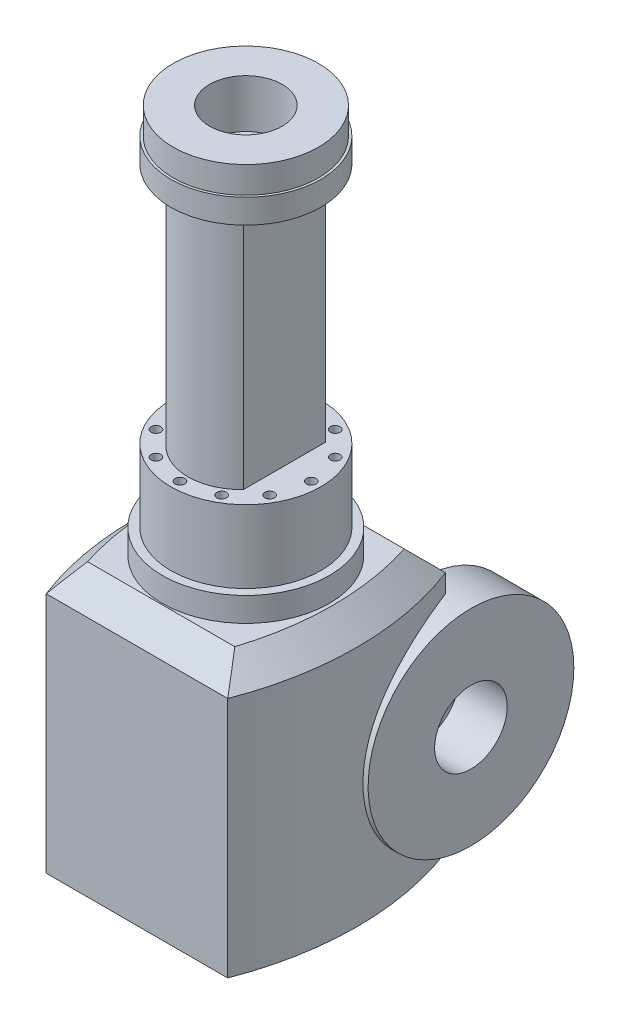
SolidWorks part; units mm, degrees
ref_plane "Front Plane" through (0, 0, 0) normal (0, 0, 1) x (1, 0, 0)
ref_plane "Top Plane" through (0, 0, 0) normal (0, 1, 0) x (1, 0, 0)
ref_plane "Right Plane" through (0, 0, 0) normal (1, 0, 0) x (0, 0, -1)
sketch "Sketch1" plane through (0, 0, 0) normal (0, 1, 0) x (1, 0, 0)
  line L0 (0, 45) -> (0, -45) construction
  line L1 (-66.3108, 0) -> (66.3108, 0) construction
  line L2 (-37.5, 45) -> (37.5, 45)
  line L3 (-37.5, -45) -> (37.5, -45)
  arc A0 (-37.5, 45) -> (-37.5, -45) centre (79.119, 0) ccw
  arc A1 (37.5, 45) -> (37.5, -45) centre (-79.119, 0) cw
  point P4 (0, 0)
  point P8 (0, 0)
  dimension "D4" = 125
  dimension "D1" = 75
  dimension "D2" = 45
  dimension "D3" = 90
extrude "Boss-Extrude1" add sketch "Sketch1" along normal blind 100
sketch "Sketch2" plane through (0, 100, 0) normal (0, 1, 0) x (1, 0, 0)
  line L2 (-37.5, -45) -> (37.5, -45)
  line L3 (37.5, 45) -> (-37.5, 45)
  line L4 (-37.5, -45) -> (37.5, -45)
  line L5 (37.5, 45) -> (-37.5, 45)
  arc A2 (-37.5, 45) -> (-37.5, -45) centre (79.119, 0) ccw
  arc A3 (37.5, -45) -> (37.5, 45) centre (-79.119, 0) ccw
  arc A4 (-37.5, 45) -> (-37.5, -45) centre (79.119, 0) ccw
  arc A5 (37.5, -45) -> (37.5, 45) centre (-79.119, 0) ccw
  dimension "D1" = 0
extrude "Boss-Extrude2" add sketch "Sketch2" along normal blind 10 draft 45
sketch "Sketch3" plane through (0, 110, 0) normal (0, 1, 0) x (1, 0, 0)
  circle A0 centre (0, 0) radius 34.5
  dimension "D1" = 69
extrude "Boss-Extrude3" add sketch "Sketch3" along normal blind 10
sketch "Sketch4" plane through (0, 120, 0) normal (0, 1, 0) x (1, 0, 0)
  circle A0 centre (0, 0) radius 31
  dimension "D1" = 62
extrude "Boss-Extrude4" add sketch "Sketch4" along normal blind 30
sketch "Sketch5" plane through (0, 150, 0) normal (0, 1, 0) x (1, 0, 0)
  line L0 (27, 0) -> (0, 0) construction
  circle A0 centre (27, 0) radius 2
  dimension "D2" = 4
  dimension "D1" = 27
extrude "Cut-Extrude1" cut sketch "Sketch5" against normal blind 5
pattern_circular "CirPattern1" count 12 over 360 about axis through (-0.1129, 0, 0) along (0, 1, 0) of "Cut-Extrude1"
sketch "Sketch6" plane through (0, 150, 0) normal (0, 1, 0) x (1, 0, 0)
  line L0 (-18.5252, 0) -> (17.8556, 0) construction
  line L1 (0, 21.134) -> (0, -18.856) construction
  line L2 (-16, -17) -> (-16, 17)
  line L3 (16, -17) -> (16, 17)
  arc A0 (-16, 17) -> (16, 17) centre (0, 1.9003) cw
  arc A1 (-16, -17) -> (16, -17) centre (0, -1.9003) ccw
  point P8 (-16, 0)
  dimension "D3" = 22
  dimension "D1" = 34
  dimension "D2" = 16
extrude "Boss-Extrude5" add sketch "Sketch6" along normal blind 100
sketch "Sketch7" plane through (0, 250, 0) normal (0, 1, 0) x (1, 0, 0)
  circle A0 centre (0, 0) radius 31
  dimension "D1" = 62
extrude "Boss-Extrude6" add sketch "Sketch7" along normal blind 10
sketch "Sketch8" plane through (0, 260, 0) normal (0, 1, 0) x (1, 0, 0)
  circle A0 centre (0, 0) radius 30
  circle A2 centre (0, 0) radius 31 construction
  dimension "D1" = 1
extrude "Boss-Extrude7" add sketch "Sketch8" along normal blind 11
ref_plane "Plane2" through (37.5, 0, 0) normal (1, 0, 0) x (0, 0, -1)
sketch "Sketch10" plane through (37.5, 0, 0) normal (1, 0, 0) x (0, 0, -1)
  line L0 (45, 100) -> (45, 0) construction
  circle A0 centre (45, 50) radius 42.5
  dimension "D1" = 85
extrude "Boss-Extrude8" add sketch "Sketch10" along normal mid plane 21
sketch "Sketch11" plane through (27, 0, 0) normal (-1, 0, 0) x (0, 0, 1)
  line L0 (-45, 50) -> (-138.4819, 50) construction
  line L1 (-45, 7.5) -> (-45, 92.5) construction
  line L2 (-45, 30) -> (-75, 30)
  line L3 (-45, 70) -> (-75, 70)
  line L4 (-45, 70) -> (-45, 30)
  arc A0 (-75, 70) -> (-75, 30) centre (-52.6393, 50) ccw
  point P8 (-60, 30)
  dimension "D3" = 30
  dimension "D1" = 30
  dimension "D2" = 20
extrude "Boss-Extrude9" add sketch "Sketch11" along normal blind 55
sketch "Sketch12" plane through (0, 271, 0) normal (0, 1, 0) x (1, 0, 0)
  circle A0 centre (0, 0) radius 15
  dimension "D1" = 30
extrude "Cut-Extrude2" cut sketch "Sketch12" against normal blind 20
sketch "Sketch13" plane through (48, 0, 0) normal (1, 0, 0) x (0, 0, -1)
  circle A0 centre (45, 50) radius 15
  dimension "D1" = 30
extrude "Cut-Extrude3" cut sketch "Sketch13" against normal blind 20
scale "Ölçek1" bodies to scale 113 scale about centroid uniform scaling yes scale factor 0.2
